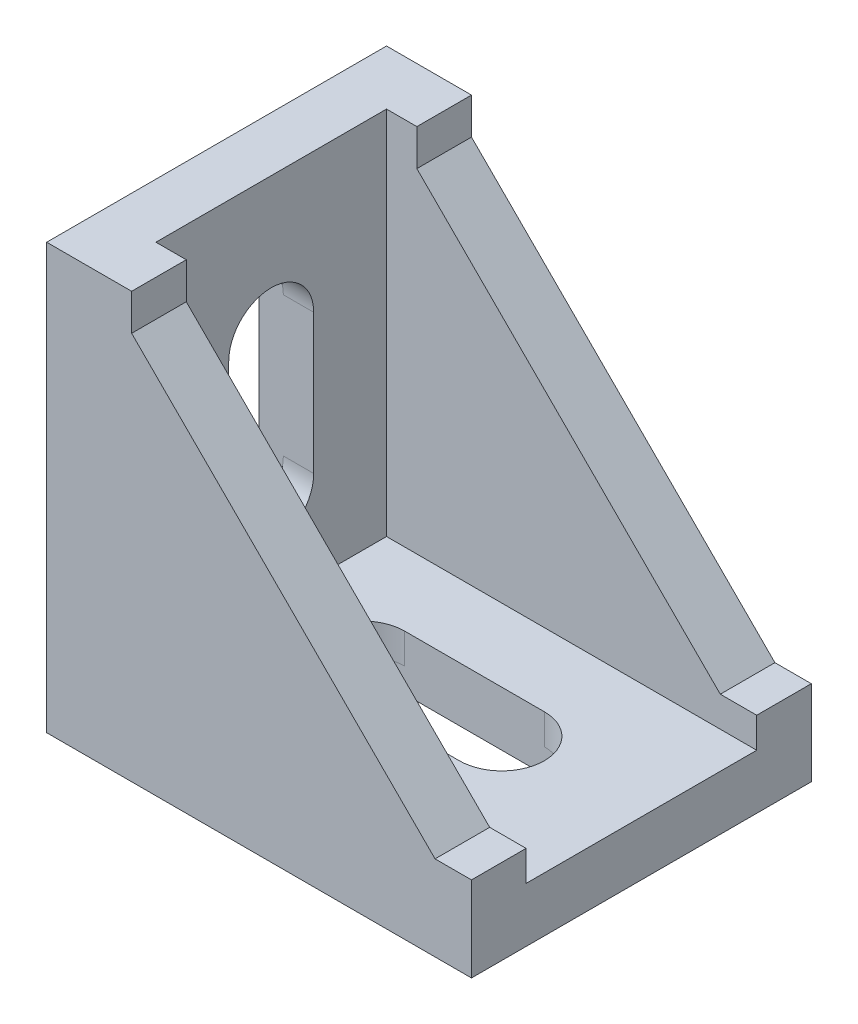
SolidWorks part; units mm, degrees
ref_plane "Front" through (0, 0, 0) normal (0, 0, 1) x (1, 0, 0)
ref_plane "Top" through (0, 0, 0) normal (0, 1, 0) x (1, 0, 0)
ref_plane "Right" through (0, 0, 0) normal (1, 0, 0) x (0, 0, -1)
sketch "Sketch1" plane through (0, 0, 0) normal (0, 1, 0) x (1, 0, 0)
  line L1 (-17.5, 14) -> (17.5, 14)
  line L2 (-17.5, 14) -> (-17.5, -14)
  line L3 (-17.5, -14) -> (17.5, -14)
  line L4 (17.5, 14) -> (17.5, -14)
  line L5 (-17.5, 14) -> (17.5, -14) construction
  line L6 (-17.5, -14) -> (17.5, 14) construction
  line L7 (-5.5, 3.5) -> (6, 3.5)
  line L8 (-5.5, -3.5) -> (6, -3.5)
  arc A0 (-5.5, 3.5) -> (-5.5, -3.5) centre (-5.5, 0) ccw
  arc A1 (6, -3.5) -> (6, 3.5) centre (6, 0) ccw
  point P0 (0, 0)
  point P8 (0, 0)
  dimension "D3" = 3.5
  dimension "D5" = 12
  dimension "D7" = 3.5
  dimension "D1" = 28
  dimension "D2" = 35
  dimension "D4" = 11.5
  dimension "D6" = 11.5
  dimension "D8" = 11.5
  dimension "D9" = 3.5
  dimension "D10" = 3.5
extrude "Boss-Extrude1" add sketch "Sketch1" along normal blind 4.5
sketch "Sketch2" plane through (0, 0, 14) normal (0, 0, 1) x (1, 0, 0)
  line L0 (17.5, 4.5) -> (17.5, 7)
  line L1 (17.5, 7) -> (14.5, 7)
  line L2 (14.5, 7) -> (-10.5, 32)
  line L3 (-10.5, 32) -> (-10.5, 35)
  line L4 (-10.5, 35) -> (-17.5, 35)
  line L5 (-17.5, 35) -> (-17.5, 4.5)
  line L6 (-17.5, 0) -> (17.5, 0) construction
  line L7 (-17.5, 4.5) -> (17.5, 4.5)
  dimension "D1" = 35
  dimension "D2" = 7
  dimension "D3" = 7
  dimension "D4" = 3
  dimension "D5" = 3
extrude "Boss-Extrude2" add sketch "Sketch2" against normal blind 4.5
mirror "Mirror1" about plane through (0, 0, 0) normal (0, 0, 1) of "Boss-Extrude2"
sketch "Sketch3" plane through (-17.5, 0, 0) normal (-1, 0, 0) x (0, 0, 1)
  line L1 (-9.5, 35) -> (9.5, 35)
  line L2 (-9.5, 35) -> (-9.5, 4.5)
  line L3 (-9.5, 4.5) -> (9.5, 4.5)
  line L4 (9.5, 35) -> (9.5, 4.5)
  line L5 (-9.5, 35) -> (9.5, 4.5) construction
  line L6 (-9.5, 4.5) -> (9.5, 35) construction
  point P4 (0, 19.75)
extrude "Boss-Extrude3" add sketch "Sketch3" against normal blind 4.5
sketch "Sketch4" plane through (-17.5, 0, 0) normal (-1, 0, 0) x (0, 0, 1)
  line L0 (0, 35) -> (0, 0) construction
  line L1 (-14, 35) -> (14, 35) construction
  line L2 (0, 23.5) -> (0, 12) construction
  line L3 (3.5, 23.5) -> (3.5, 12)
  line L4 (-3.5, 23.5) -> (-3.5, 12)
  line L5 (-14, 0) -> (14, 0) construction
  arc A0 (3.5, 23.5) -> (-3.5, 23.5) centre (0, 23.5) ccw
  arc A1 (-3.5, 12) -> (3.5, 12) centre (0, 12) ccw
  point P7 (0, 17.75)
  dimension "D1" = 3.5
  dimension "D3" = 12
  dimension "D2" = 11.5
extrude "Cut-Extrude1" cut sketch "Sketch4" against normal blind 4.5
sketch "Sketch5" plane through (-17.5, 0, 0) normal (-1, 0, 0) x (0, 0, 1)
  line L0 (-3.5, 17.75) -> (3.5, 17.75) construction
  line L1 (-3.5, 23.5) -> (-3.5, 12) construction
  line L2 (3.5, 12) -> (3.5, 23.5) construction
  line L3 (0, 35) -> (0, 0) construction
  line L4 (-3.5, 29.25) -> (3.5, 29.25)
  line L5 (-3.5, 29.25) -> (-3.5, 6.25)
  line L6 (-3.5, 6.25) -> (3.5, 6.25)
  line L7 (3.5, 29.25) -> (3.5, 6.25)
  line L8 (-3.5, 29.25) -> (3.5, 6.25) construction
  line L9 (-3.5, 6.25) -> (3.5, 29.25) construction
  line L10 (-11.5, 32.75) -> (-8.5, 32.75)
  line L11 (-11.5, 32.75) -> (-11.5, 2.75)
  line L12 (-11.5, 2.75) -> (-8.5, 2.75)
  line L13 (-8.5, 32.75) -> (-8.5, 2.75)
  line L14 (-11.5, 32.75) -> (-8.5, 2.75) construction
  line L15 (-11.5, 2.75) -> (-8.5, 32.75) construction
  line L16 (-14, 35) -> (14, 35) construction
  line L17 (11.5, 2.75) -> (8.5, 2.75)
  line L18 (8.5, 32.75) -> (8.5, 2.75)
  line L19 (11.5, 32.75) -> (8.5, 32.75)
  line L20 (11.5, 32.75) -> (11.5, 2.75)
  point P6 (0, 17.75)
  point P11 (-10, 17.75)
  dimension "D1" = 23
  dimension "D2" = 30
  dimension "D3" = 3
  dimension "D4" = 10
extrude "Cut-Extrude2" cut sketch "Sketch5" against normal blind 2
sketch "Sketch6" plane through (0, 0, 0) normal (0, 0, 1) x (1, 0, 0)
  line L1 (-17.5, 35) -> (-17.5, 0) construction
  line L2 (-17.5, 4.8) -> (-18.9, 4.8)
  line L3 (-19.02, 5.16) -> (-15.5, 7.8)
  line L4 (-15.5, 7.8) -> (-15.5, 4.8)
  line L5 (-15.5, 4.8) -> (-17.5, 4.8)
  line L7 (-17.5, 29.25) -> (-19.0172, 29.25)
  line L8 (-17.5, 6.25) -> (-17.5, 29.25) construction
  line L9 (-19.1586, 29.5914) -> (-17.5, 31.25)
  line L10 (-17.5, 31.25) -> (-17.5, 29.25)
  line L11 (-17.5, 0) -> (17.5, 0) construction
  arc A0 (-18.9, 4.8) -> (-19.02, 5.16) centre (-18.9, 5) cw
  arc A1 (-19.0172, 29.25) -> (-19.1586, 29.5914) centre (-19.0172, 29.45) cw
  point P13 (-19.5, 4.8)
  dimension "D4" = 0.2
  dimension "D1" = 2
  dimension "D2" = 2
  dimension "D3" = 2
  dimension "D5" = 4.8
extrude "Boss-Extrude4" add sketch "Sketch6" along normal mid plane 6
ref_plane "Plane1" through (-8.75, 8.75, 0) normal (-0.7071, 0.7071, 0) x (0.7071, 0.7071, 0)
mirror "Mirror2" about plane through (-8.75, 8.75, 0) normal (-0.7071, 0.7071, 0) of "Cut-Extrude2", "Boss-Extrude4", "Cut-Extrude1"
